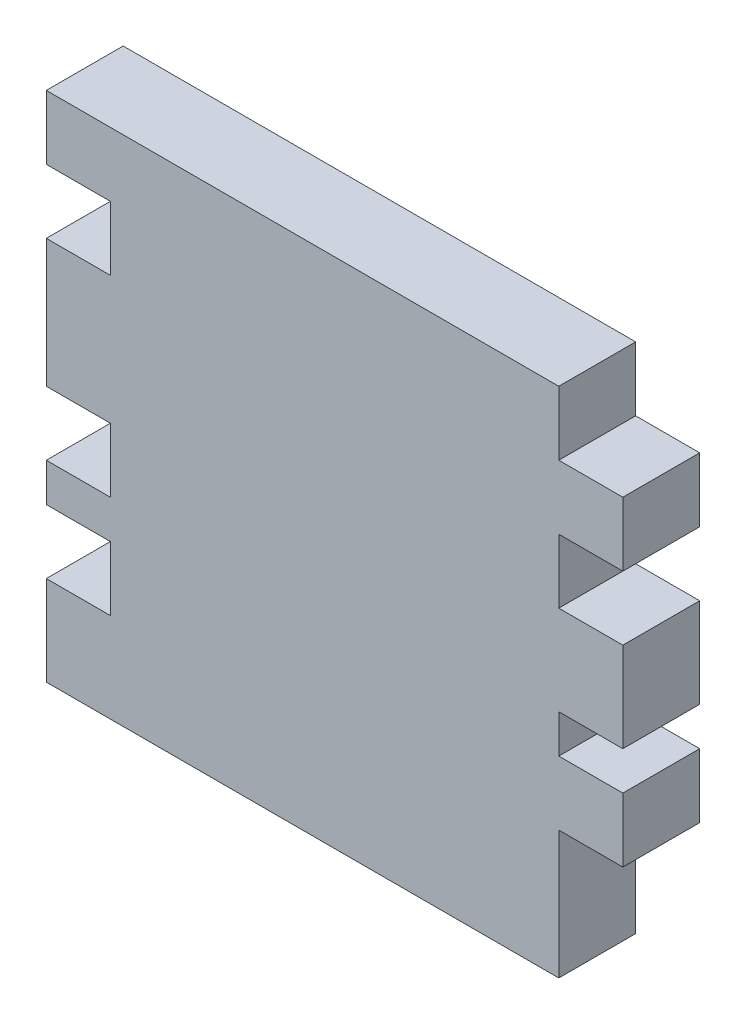
SolidWorks part; units mm, degrees
ref_plane "Front Plane" through (0, 0, 0) normal (0, 0, 1) x (1, 0, 0)
ref_plane "Top Plane" through (0, 0, 0) normal (0, 1, 0) x (1, 0, 0)
ref_plane "Right Plane" through (0, 0, 0) normal (1, 0, 0) x (0, 0, -1)
sketch "Sketch1" plane through (0, 0, 0) normal (0, 0, 1) x (1, 0, 0)
  line L1 (-21.2611, 17.3845) -> (23.7389, 17.3845)
  line L2 (-21.2611, 17.3845) -> (-21.2611, -22.6155)
  line L3 (-21.2611, -22.6155) -> (23.7389, -22.6155)
  line L4 (23.7389, 17.3845) -> (23.7389, -22.6155)
  dimension "D1" = 45
  dimension "D2" = 40
extrude "Boss-Extrude1" add sketch "Sketch1" along normal blind 6 contours L2 L1 L4 L3
sketch "Sketch2" plane through (0, 0, 6) normal (0, 0, 1) x (1, 0, 0)
  line L0 (-21.2611, 17.3845) -> (-21.2611, -22.6155) construction
  line L1 (-21.2611, 7.3845) -> (-16.2611, 7.3845)
  line L2 (-21.2611, 7.3845) -> (-21.2611, 2.3845)
  line L3 (-21.2611, 2.3845) -> (-16.2611, 2.3845)
  line L4 (-16.2611, 7.3845) -> (-16.2611, 2.3845)
  line L5 (-21.2611, 17.3845) -> (23.7389, 17.3845) construction
  line L6 (-21.2611, -0.6155) -> (-16.2611, -0.6155)
  line L7 (-21.2611, -0.6155) -> (-21.2611, -7.6155)
  line L8 (-21.2611, -7.6155) -> (-16.2611, -7.6155)
  line L9 (-16.2611, -0.6155) -> (-16.2611, -7.6155)
  line L10 (-21.2611, -12.6155) -> (-16.2611, -12.6155)
  line L11 (-21.2611, -12.6155) -> (-21.2611, -17.6155)
  line L12 (-21.2611, -17.6155) -> (-16.2611, -17.6155)
  line L13 (-16.2611, -12.6155) -> (-16.2611, -17.6155)
  dimension "D1" = 5
  dimension "D2" = 10
  dimension "D3" = 7
  dimension "D4" = 3
  dimension "D5" = 5
  dimension "D6" = 5
  dimension "D7" = 5
  dimension "D8" = 5
  dimension "D9" = 5
extrude "Cut-Extrude1" cut sketch "Sketch2" against normal blind 6 contours L2 L1 L4 L3 | L7 L6 L9 L8 | L11 L10 L13 L12
sketch "Sketch3" plane through (0, 0, 6) normal (0, 0, 1) x (1, 0, 0)
  line L0 (23.7389, 17.3845) -> (23.7389, -22.6155) construction
  line L1 (23.7389, -17.6155) -> (18.7389, -17.6155)
  line L2 (23.7389, -17.6155) -> (23.7389, -22.6155)
  line L3 (23.7389, -22.6155) -> (18.7389, -22.6155)
  line L4 (18.7389, -17.6155) -> (18.7389, -22.6155)
  line L5 (-21.2611, -22.6155) -> (23.7389, -22.6155) construction
  line L6 (-21.2611, 17.3845) -> (23.7389, 17.3845) construction
  line L7 (23.7389, -7.6155) -> (18.7389, -7.6155)
  line L8 (23.7389, -7.6155) -> (23.7389, -10.6155)
  line L9 (23.7389, -10.6155) -> (18.7389, -10.6155)
  line L10 (18.7389, -7.6155) -> (18.7389, -10.6155)
  line L15 (23.7389, 12.3845) -> (18.7389, 12.3845)
  line L16 (23.7389, 12.3845) -> (23.7389, 17.3845)
  line L17 (23.7389, 17.3845) -> (18.7389, 17.3845)
  line L18 (18.7389, 12.3845) -> (18.7389, 17.3845)
  line L20 (23.7389, 7.3845) -> (18.7389, 7.3845)
  line L21 (23.7389, 7.3845) -> (23.7389, -2.6155)
  line L22 (23.7389, -2.6155) -> (18.7389, -2.6155)
  line L23 (18.7389, 7.3845) -> (18.7389, -2.6155)
  dimension "D1" = 5
  dimension "D2" = 5
  dimension "D3" = 5
  dimension "D4" = 10
  dimension "D5" = 5
  dimension "D6" = 3
  dimension "D7" = 7
extrude "Cut-Extrude2" cut sketch "Sketch3" against normal blind 6 contours L16 L15 L18 L17 | L21 L20 L23 L22 | L8 L7 L10 L9 | L2 L1 L4 L3
sketch "Sketch4" plane through (0, 0, 6) normal (0, 0, 1) x (1, 0, 0)
  line L1 (-21.2611, 7.3845) -> (-16.2611, 7.3845)
  line L2 (-21.2611, 7.3845) -> (-21.2611, -17.6155)
  line L3 (-21.2611, -17.6155) -> (-16.2611, -17.6155)
  line L4 (-16.2611, 7.3845) -> (-16.2611, -17.6155)
extrude "Boss-Extrude3" add sketch "Sketch4" against normal blind 6
sketch "Sketch8" plane through (0, 0, 6) normal (0, 0, 1) x (1, 0, 0)
  line L9 (-21.2611, -7.6155) -> (-16.2611, -7.6155)
  line L18 (-21.2611, 17.3845) -> (-21.2611, -22.6155) construction
  line L23 (-21.2611, -10.6155) -> (-16.2611, -10.6155)
  line L24 (-21.2611, -10.6155) -> (-21.2611, -15.6155)
  line L25 (-21.2611, -15.6155) -> (-16.2611, -15.6155)
  line L26 (-16.2611, -10.6155) -> (-16.2611, -15.6155)
  line L27 (-21.2611, -22.6155) -> (18.7389, -22.6155) construction
  line L28 (-21.2611, -7.6155) -> (-21.2611, -2.6155)
  line L29 (-21.2611, -2.6155) -> (-16.2611, -2.6155)
  line L30 (-16.2611, -7.6155) -> (-16.2611, -2.6155)
  line L31 (-21.2611, 7.3845) -> (-16.2611, 7.3845)
  line L32 (-21.2611, 7.3845) -> (-21.2611, 12.3845)
  line L33 (-21.2611, 12.3845) -> (-16.2611, 12.3845)
  line L34 (-16.2611, 7.3845) -> (-16.2611, 12.3845)
  dimension "D1" = 5
  dimension "D2" = 5
  dimension "D3" = 7
  dimension "D4" = 5
  dimension "D5" = 3
  dimension "D6" = 5
  dimension "D7" = 10
extrude "Cut-Extrude5" cut sketch "Sketch8" against normal blind 6 contours L32 L31 L34 L33 | L28 L9 L30 L29 | L24 L23 L26 L25
sketch "Sketch9" plane through (0, 0, 6) normal (0, 0, 1) x (1, 0, 0)
  line L1 (18.7389, 17.3845) -> (23.7389, 17.3845)
  line L2 (18.7389, 17.3845) -> (18.7389, -22.6155)
  line L3 (18.7389, -22.6155) -> (23.7389, -22.6155)
  line L4 (23.7389, 17.3845) -> (23.7389, -22.6155)
  dimension "D1" = 5
  dimension "D2" = 40
extrude "Boss-Extrude4" add sketch "Sketch9" against normal blind 6
sketch "Sketch10" plane through (0, 0, 6) normal (0, 0, 1) x (1, 0, 0)
  line L0 (23.7389, 17.3845) -> (23.7389, -22.6155) construction
  line L1 (23.7389, 17.3845) -> (18.7389, 17.3845)
  line L2 (23.7389, 17.3845) -> (23.7389, 12.3845)
  line L3 (23.7389, 12.3845) -> (18.7389, 12.3845)
  line L4 (18.7389, 17.3845) -> (18.7389, 12.3845)
  line L5 (23.7389, 7.3845) -> (18.7389, 7.3845)
  line L6 (23.7389, 7.3845) -> (23.7389, 2.3845)
  line L7 (23.7389, 2.3845) -> (18.7389, 2.3845)
  line L8 (18.7389, 7.3845) -> (18.7389, 2.3845)
  line L9 (-21.2611, -22.6155) -> (23.7389, -22.6155) construction
  line L10 (23.7389, -4.6155) -> (18.7389, -4.6155)
  line L11 (23.7389, -4.6155) -> (23.7389, -7.6155)
  line L12 (23.7389, -7.6155) -> (18.7389, -7.6155)
  line L13 (18.7389, -4.6155) -> (18.7389, -7.6155)
  line L14 (23.7389, -12.6155) -> (18.7389, -12.6155)
  line L15 (23.7389, -12.6155) -> (23.7389, -22.6155)
  line L16 (23.7389, -22.6155) -> (18.7389, -22.6155)
  line L17 (18.7389, -12.6155) -> (18.7389, -22.6155)
  dimension "D1" = 5
  dimension "D2" = 5
  dimension "D3" = 5
  dimension "D4" = 5
  dimension "D5" = 7
  dimension "D6" = 3
  dimension "D7" = 10
extrude "Cut-Extrude7" cut sketch "Sketch10" against normal blind 6 contours L2 L1 L4 L3 | L6 L5 L8 L7 | L11 L10 L13 L12 | L15 L14 L17 L16
